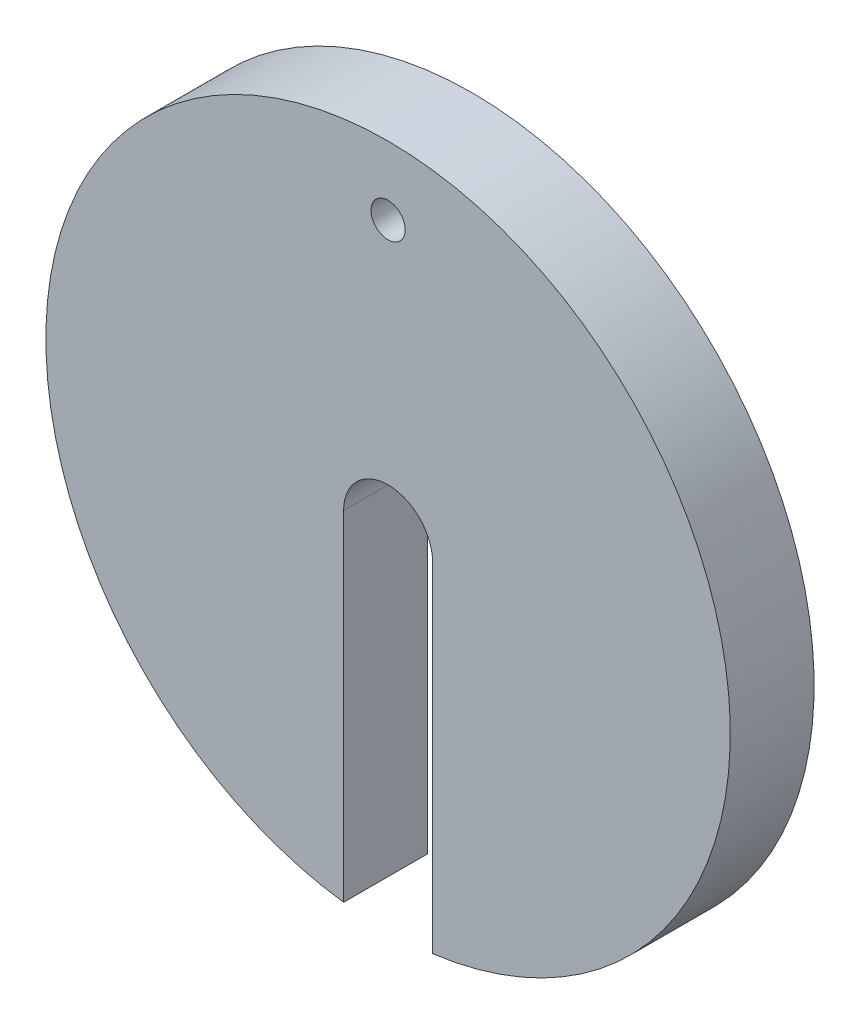
SolidWorks part; units mm, degrees
ref_plane "Face" through (0, 0, 0) normal (0, 0, 1) x (1, 0, 0)
ref_plane "Dessus" through (0, 0, 0) normal (0, 1, 0) x (1, 0, 0)
ref_plane "Droite" through (0, 0, 0) normal (1, 0, 0) x (0, 0, -1)
sketch "Esquisse1" plane through (0, 0, 0) normal (0, 0, 1) x (1, 0, 0)
  line L0 (-6.5, 0) -> (-6.5, -49.5757)
  line L1 (6.5, 0) -> (6.5, -49.5757)
  line L2 (0, 0) -> (0, 45.082) construction
  arc A0 (6.5, -49.5757) -> (-6.5, -49.5757) centre (0, 0) ccw
  arc A1 (6.5, 0) -> (-6.5, 0) centre (0, 0) ccw
  circle A2 centre (0, 40) radius 2.5
  dimension "D1" = 13
  dimension "D2" = 100
  dimension "D3" = 5
  dimension "D4" = 40
extrude "Base-Extrusion" add sketch "Esquisse1" along normal blind 12.25
